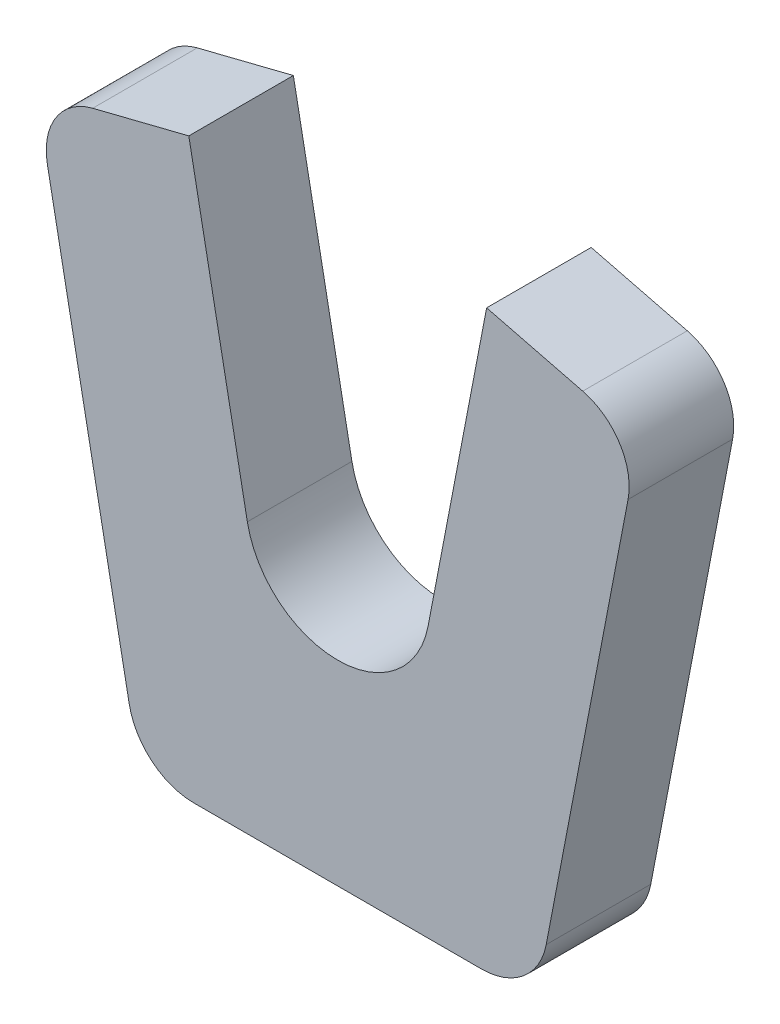
SolidWorks part; units mm, degrees
ref_plane "Alzado" through (0, 0, 0) normal (0, 0, 1) x (1, 0, 0)
ref_plane "Planta" through (0, 0, 0) normal (0, 1, 0) x (1, 0, 0)
ref_plane "Vista lateral" through (0, 0, 0) normal (1, 0, 0) x (0, 0, -1)
sketch "Croquis1" plane through (0, 0, 0) normal (0, 0, 1) x (1, 0, 0)
  line L0 (0, 0) -> (0, 55) construction
  line L1 (-13.75, 0) -> (13.75, 0)
  line L2 (19.937, 5.1124) -> (27.7653, 45.8933)
  line L3 (23.4289, 52.694) -> (14.2395, 55)
  line L4 (14.2395, 55) -> (8.6422, 25.8411)
  line L5 (-23.4289, 52.694) -> (-14.2395, 55)
  line L6 (-14.2395, 55) -> (-8.6422, 25.8411)
  line L7 (-19.937, 5.1124) -> (-27.7653, 45.8933)
  arc A0 (-8.6422, 25.8411) -> (8.6422, 25.8411) centre (0, 27.5) ccw
  arc A1 (13.75, 0) -> (19.937, 5.1124) centre (13.75, 6.3) ccw
  arc A2 (27.7653, 45.8933) -> (23.4289, 52.694) centre (22, 47) ccw
  arc A3 (-13.75, 0) -> (-19.937, 5.1124) centre (-13.75, 6.3) cw
  arc A4 (-27.7653, 45.8933) -> (-23.4289, 52.694) centre (-22, 47) cw
  dimension "D3" = 8.8
  dimension "D6" = 6.3
  dimension "D7" = 22
  dimension "D1" = 55
  dimension "D2" = 13.75
  dimension "D4" = 27.5
  dimension "D5" = 15
  dimension "D8" = 47
extrude "Saliente-Extruir1" add sketch "Croquis1" along normal blind 10
